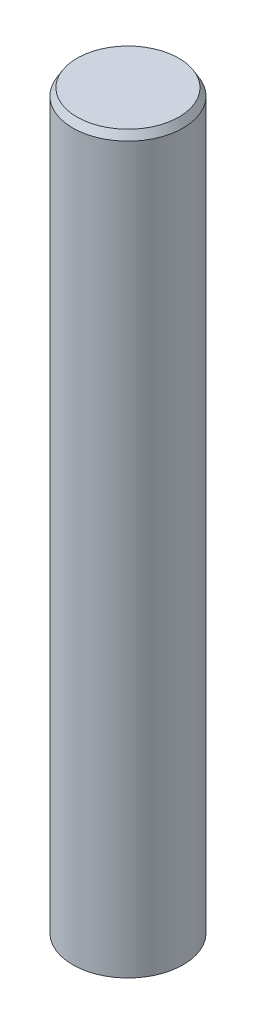
SolidWorks part; units mm, degrees
material "AISI 304"
ref_plane "Front Plane" through (0, 0, 0) normal (0, 0, 1) x (1, 0, 0)
ref_plane "Top Plane" through (0, 0, 0) normal (0, 1, 0) x (1, 0, 0)
ref_plane "Right Plane" through (0, 0, 0) normal (1, 0, 0) x (0, 0, -1)
sketch "Sketch1" plane through (0, 0, 0) normal (0, 1, 0) x (1, 0, 0)
  circle A0 centre (0, 0) radius 1.5
  dimension "D1" = 3
extrude "Boss-Extrude1" add sketch "Sketch1" along normal blind 20
chamfer "Chamfer1" distance 0.2 angle 30 2 edges at (0, 0, 1.5) (0, 20, 1.5)
